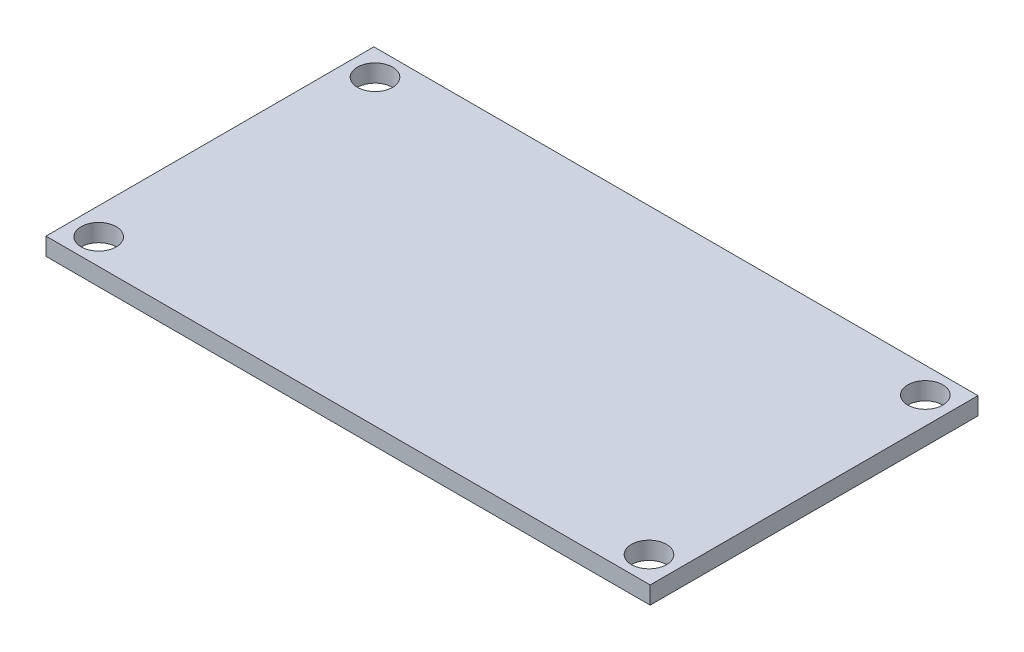
SolidWorks part; units mm, degrees
ref_plane "Front Plane" through (0, 0, 0) normal (0, 0, 1) x (1, 0, 0)
ref_plane "Top Plane" through (0, 0, 0) normal (0, 1, 0) x (1, 0, 0)
ref_plane "Right Plane" through (0, 0, 0) normal (1, 0, 0) x (0, 0, -1)
sketch "Sketch1" plane through (0, 0, 0) normal (0, 1, 0) x (1, 0, 0)
  line L1 (0, 0) -> (51.6, 0)
  line L2 (0, 0) -> (0, -28)
  line L3 (0, -28) -> (51.6, -28)
  line L4 (51.6, 0) -> (51.6, -28)
  dimension "D1" = 28
  dimension "D2" = 51.6
extrude "Boss-Extrude1" add sketch "Sketch1" along normal blind 1.5
sketch "Sketch2" plane through (0, 1.5, 0) normal (0, 1, 0) x (1, 0, 0)
  line L0 (51.6, 0) -> (0, 0) construction
  line L1 (0, 0) -> (0, -28) construction
  circle A0 centre (2.3, -2.2) radius 1.5
  circle A1 centre (49.3, -2.2) radius 1.5
  circle A2 centre (49.3, -25.8) radius 1.5
  circle A3 centre (2.3, -25.8) radius 1.5
  point P2 (0, 0)
  dimension "D1" = 3
  dimension "D4" = 2.2
  dimension "D5" = 2.3
  dimension "D2" = 2
  dimension "D3" = 2
extrude "Cut-Extrude1" cut sketch "Sketch2" against normal blind 1.5
